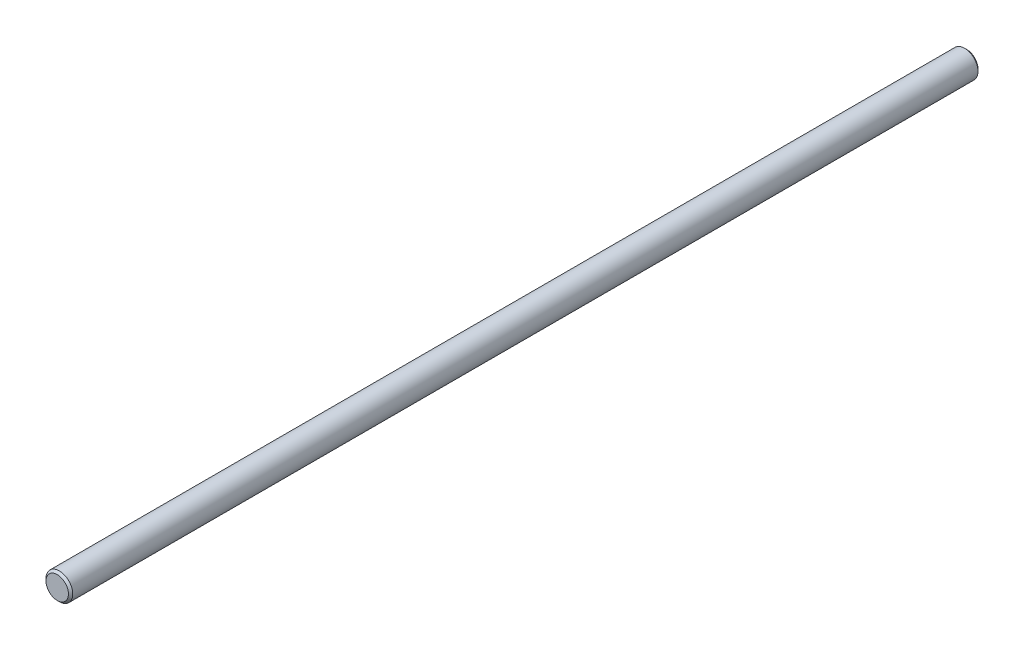
SolidWorks part; units mm, degrees
material "1.4301 (X5CrNi18-10)"
ref_plane "Vorne" through (0, 0, 0) normal (0, 0, 1) x (1, 0, 0)
ref_plane "Oben" through (0, 0, 0) normal (0, 1, 0) x (1, 0, 0)
ref_plane "Rechts" through (0, 0, 0) normal (1, 0, 0) x (0, 0, -1)
sketch "Skizze1" plane through (0, 0, 0) normal (0, 0, 1) x (1, 0, 0)
  circle A0 centre (0, 0) radius 2.5
  dimension "D1" = 5
extrude "Aufsatz-Linear austragen1" add sketch "Skizze1" along normal mid plane 170
cosmetic thread "Gewindedarstellung1" parameters "D1"=10, "D2"=4.11
cosmetic thread "Gewindedarstellung2" parameters "D1"=10, "D2"=4.11
chamfer "Fase1" distance 0.4 angle 45 2 edges at (2.5, 0, -85) (2.5, 0, 85)
